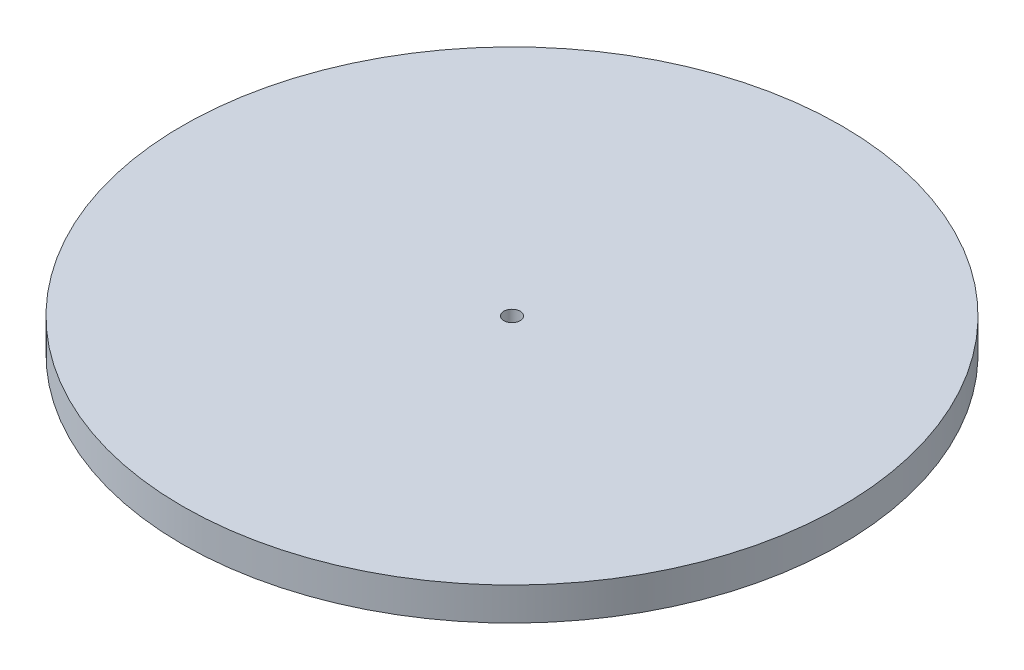
SolidWorks part; units mm, degrees
ref_plane "Front Plane" through (0, 0, 0) normal (0, 0, 1) x (1, 0, 0)
ref_plane "Top Plane" through (0, 0, 0) normal (0, 1, 0) x (1, 0, 0)
ref_plane "Right Plane" through (0, 0, 0) normal (1, 0, 0) x (0, 0, -1)
sketch "Sketch1" plane through (0, 0, 0) normal (0, 1, 0) x (1, 0, 0)
  circle A0 centre (0, 0) radius 200
  circle A1 centre (0, 0) radius 5
extrude "Boss-Extrude1" add sketch "Sketch1" along normal blind 20
